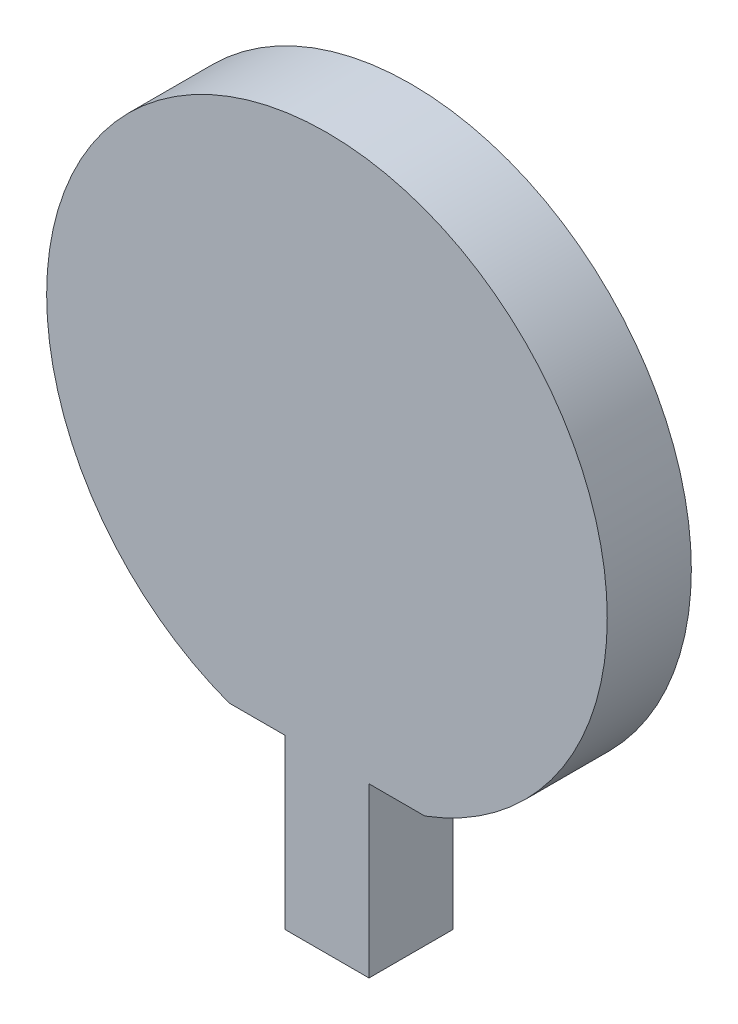
SolidWorks part; units mm, degrees
ref_plane "Front Plane" through (0, 0, 0) normal (0, 0, 1) x (1, 0, 0)
ref_plane "Top Plane" through (0, 0, 0) normal (0, 1, 0) x (1, 0, 0)
ref_plane "Right Plane" through (0, 0, 0) normal (1, 0, 0) x (0, 0, -1)
sketch "Sketch1" plane through (0, 0, 0) normal (0, 0, 1) x (1, 0, 0)
  line L5 (-9.9529, 30) -> (0, 30)
  line L6 (0, 30) -> (0, 0)
  line L7 (0, 0) -> (15, 0)
  line L8 (15, 0) -> (15, 30)
  line L9 (15, 30) -> (24.9529, 30)
  arc A1 (-9.9529, 30) -> (24.9529, 30) centre (7.5, 76.8551) cw
  dimension "D1" = 50
  dimension "D2" = 30
  dimension "D3" = 15
extrude "Boss-Extrude1" add sketch "Sketch1" along normal blind 15
